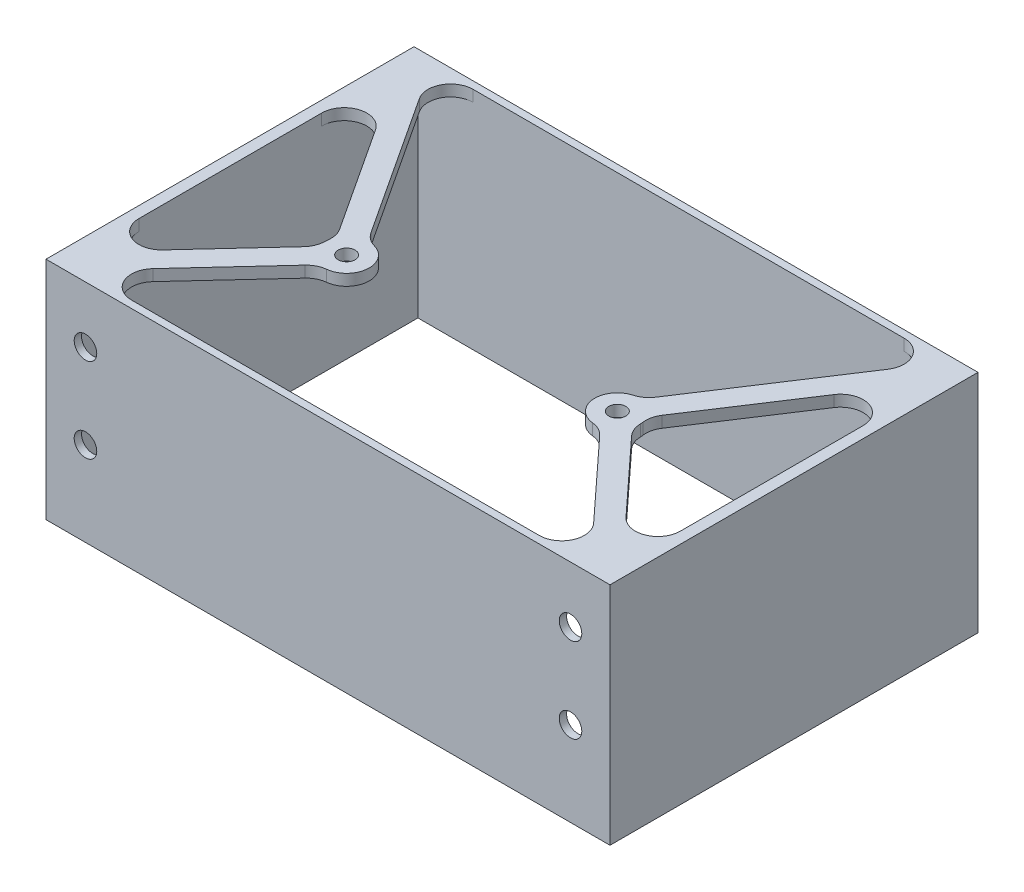
SolidWorks part; units mm, degrees
ref_plane "Front Plane" through (0, 0, 0) normal (0, 0, 1) x (1, 0, 0)
ref_plane "Top Plane" through (0, 0, 0) normal (0, 1, 0) x (1, 0, 0)
ref_plane "Right Plane" through (0, 0, 0) normal (1, 0, 0) x (0, 0, -1)
sketch "Sketch1" plane through (0, 0, 0) normal (0, 1, 0) x (1, 0, 0)
  line L1 (50, -32.625) -> (-50, -32.625)
  line L2 (50, -32.625) -> (50, 32.625)
  line L3 (50, 32.625) -> (-50, 32.625)
  line L4 (-50, -32.625) -> (-50, 32.625)
  line L5 (50, -32.625) -> (-50, 32.625) construction
  line L6 (50, 32.625) -> (-50, -32.625) construction
  line L7 (-48, -31.32) -> (48, -31.32)
  line L8 (-48, -31.32) -> (-48, 31.32)
  line L9 (-48, 31.32) -> (48, 31.32)
  line L10 (48, -31.32) -> (48, 31.32)
  line L11 (-48, -31.32) -> (48, 31.32) construction
  line L12 (-48, 31.32) -> (48, -31.32) construction
  point P0 (0, 0)
  point P6 (0, 0)
  dimension "D1" = 2
  dimension "D2" = 100
  dimension "D3" = 65.25
extrude "Boss-Extrude1" add sketch "Sketch1" along normal blind 40
sketch "Sketch2" plane through (0, 0, 32.625) normal (0, 0, 1) x (1, 0, 0)
  line L0 (50, 40) -> (50, 0) construction
  line L1 (-50, 40) -> (-50, 0) construction
  line L2 (-50, 40) -> (50, 40) construction
  circle A0 centre (-43, 15) radius 2
  circle A1 centre (-43, 30) radius 2
  circle A2 centre (43, 30) radius 2
  circle A3 centre (43, 15) radius 2
  dimension "D3" = 4
  dimension "D1" = 15
  dimension "D2" = 15
  dimension "D4" = 7
  dimension "D5" = 7
  dimension "D6" = 10
  dimension "D7" = 10
extrude "Cut-Extrude1" cut sketch "Sketch2" against normal up to next
sketch "Sketch3" plane through (0, 40, 0) normal (0, 1, 0) x (1, 0, 0)
  line L0 (-48, -31.32) -> (48, -31.32) construction
  line L7 (-24, -5.32) -> (24, -5.32) construction
  circle A0 centre (-24, -5.32) radius 1.5
  circle A1 centre (24, -5.32) radius 1.5
  circle A2 centre (-24, -5.32) radius 4
  circle A3 centre (24, -5.32) radius 4
  point P0 (0, 0)
  point P13 (0, -5.32)
  dimension "D1" = 26
  dimension "D2" = 3
  dimension "D4" = 8
  dimension "D3" = 48
extrude "Boss-Extrude2" add sketch "Sketch3" against normal blind 2
sketch "Sketch4" plane through (0, 40, 0) normal (0, -1, 0) x (-1, 0, 0)
  line L6 (-48, 31.32) -> (-24, -5.32) construction
  line L9 (-24, -5.32) -> (-48, -31.32) construction
  line L26 (48, -31.32) -> (-48, -31.32) construction
  line L27 (-48, -31.32) -> (-48, 31.32) construction
  line L28 (48, 31.32) -> (24, -5.32) construction
  line L29 (24, -5.32) -> (48, -31.32) construction
  line L30 (-24, -5.32) -> (24, -5.32) construction
  line L31 (-24.2251, -1.3263) -> (-45.6091, 31.32)
  line L32 (-48, 31.32) -> (48, 31.32) construction
  line L33 (-45.6091, 31.32) -> (-48, 31.32)
  line L34 (-48, 31.32) -> (-48, 27.67)
  line L35 (-48, 27.67) -> (-27.5712, -3.5181)
  line L36 (-27.8192, -6.5089) -> (-48, -28.3714)
  line L37 (-48, -28.3714) -> (-48, -31.32)
  line L38 (-48, -31.32) -> (-45.2782, -31.32)
  line L39 (-45.2782, -31.32) -> (-24.88, -9.222)
  line L40 (24.2251, -1.3263) -> (45.6091, 31.32)
  line L41 (45.6091, 31.32) -> (48, 31.32)
  line L42 (48, 31.32) -> (48, 27.67)
  line L43 (48, 31.32) -> (48, -31.32) construction
  line L44 (48, 27.67) -> (27.5712, -3.5181)
  line L45 (48, -28.3714) -> (48, -31.32)
  line L46 (48, -31.32) -> (45.2782, -31.32)
  line L47 (45.2782, -31.32) -> (24.88, -9.222)
  line L48 (48, -28.3714) -> (27.8192, -6.5089)
  arc A0 (24.88, -9.222) -> (27.8192, -6.5089) centre (24, -5.32) ccw
  arc A1 (-27.8192, -6.5089) -> (-24.88, -9.222) centre (-24, -5.32) ccw
  arc A11 (-24.2251, -1.3263) -> (-27.5712, -3.5181) centre (-24, -5.32) ccw
  circle A12 centre (-24, -5.32) radius 4 construction
  circle A13 centre (24, -5.32) radius 4 construction
  arc A16 (27.5712, -3.5181) -> (24.2251, -1.3263) centre (24, -5.32) ccw
  dimension "D1" = 4
  dimension "D2" = 4
  dimension "D4" = 4
  dimension "D5" = 4
extrude "Boss-Extrude4" add sketch "Sketch4" along normal up to surface (2 mm away) up to face at (24, 38, 6.82)
fillet "Fillet1" radius 4 16 edges at (-27.8192, 39, 6.5089) (-27.5712, 39, 3.5181) (-48, 39, 28.3714) (-48, 39, -27.67) (-45.6091, 39, -31.32) (45.6091, 39, -31.32) (-45.2782, 39, 31.32) (45.2782, 39, 31.32) (48, 39, 28.3714) (48, 39, -27.67) (27.5712, 39, 3.5181) (27.8192, 39, 6.5089) (-24.88, 39, 9.222) (-24.2251, 39, 1.3263) (24.88, 39, 9.222) (24.2251, 39, 1.3263)
